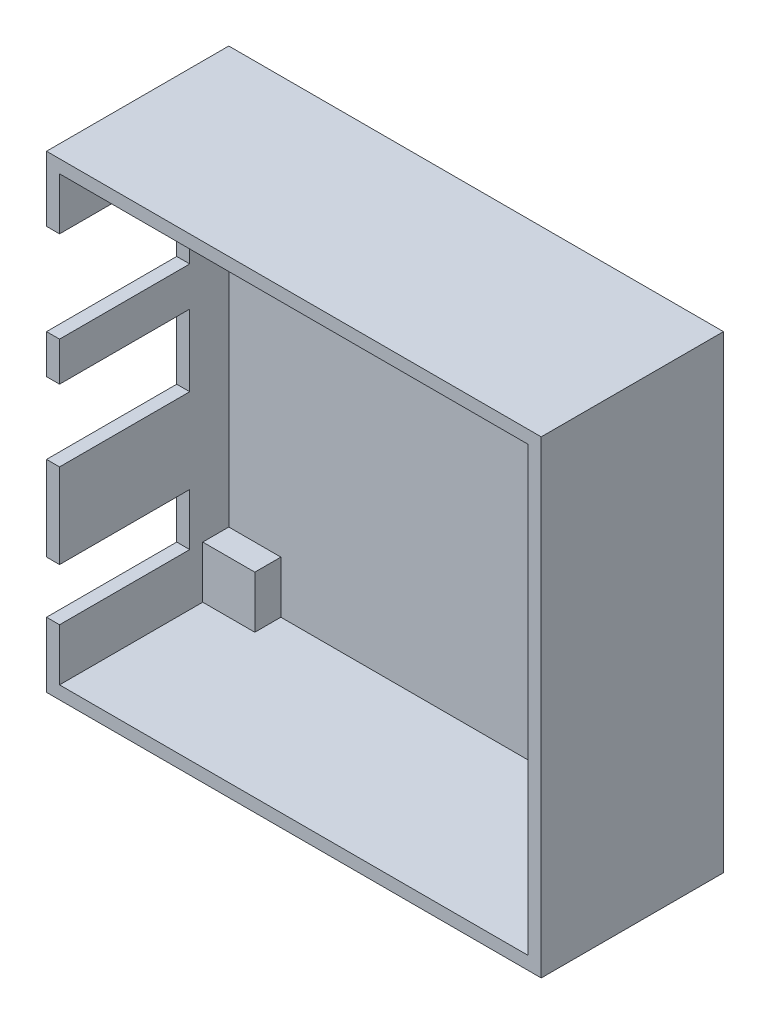
SolidWorks part; units mm, degrees
ref_plane "Plan de face" through (0, 0, 0) normal (0, 0, 1) x (1, 0, 0)
ref_plane "Plan de dessus" through (0, 0, 0) normal (0, 1, 0) x (1, 0, 0)
ref_plane "Plan de droite" through (0, 0, 0) normal (1, 0, 0) x (0, 0, -1)
sketch "Esquisse1" plane through (0, 0, 0) normal (0, 0, 1) x (1, 0, 0)
  line L1 (-70.1386, 46.5558) -> (5.8614, 46.5558)
  line L2 (-70.1386, 46.5558) -> (-70.1386, -25.4442)
  line L3 (-70.1386, -25.4442) -> (5.8614, -25.4442)
  line L4 (5.8614, 46.5558) -> (5.8614, -25.4442)
  dimension "D1" = 72
  dimension "D2" = 76
extrude "Boss.-Extru.1" add sketch "Esquisse1" along normal blind 2
sketch "Esquisse2" plane through (0, 0, 2) normal (0, 0, 1) x (1, 0, 0)
  line L1 (-70.1386, 46.5558) -> (5.8614, 46.5558)
  line L2 (-70.1386, 46.5558) -> (-70.1386, -25.4442)
  line L3 (-70.1386, -25.4442) -> (5.8614, -25.4442)
  line L4 (5.8614, 46.5558) -> (5.8614, -25.4442)
  line L5 (-68.1386, 44.5558) -> (3.8614, 44.5558)
  line L6 (-68.1386, 44.5558) -> (-68.1386, -23.4442)
  line L7 (-68.1386, -23.4442) -> (3.8614, -23.4442)
  line L8 (3.8614, 44.5558) -> (3.8614, -23.4442)
  dimension "D1" = 2
  dimension "D2" = 2
  dimension "D3" = 2
  dimension "D4" = 2
extrude "Boss.-Extru.2" add sketch "Esquisse2" along normal blind 26
sketch "Esquisse3" plane through (0, 0, 2) normal (0, 0, 1) x (1, 0, 0)
  line L0 (-68.1386, 44.5558) -> (-68.1386, -23.4442) construction
  line L1 (-68.1386, 44.5558) -> (-60.1386, 44.5558)
  line L2 (-68.1386, 44.5558) -> (-68.1386, 36.5558)
  line L3 (-68.1386, 36.5558) -> (-60.1386, 36.5558)
  line L4 (-60.1386, 44.5558) -> (-60.1386, 36.5558)
  line L5 (3.8614, -23.4442) -> (-4.1386, -23.4442)
  line L6 (3.8614, -23.4442) -> (3.8614, -15.4442)
  line L7 (3.8614, -15.4442) -> (-4.1386, -15.4442)
  line L8 (-4.1386, -23.4442) -> (-4.1386, -15.4442)
  line L9 (3.8614, 44.5558) -> (-4.1386, 44.5558)
  line L10 (3.8614, 44.5558) -> (3.8614, 36.5558)
  line L11 (3.8614, 36.5558) -> (-4.1386, 36.5558)
  line L12 (-4.1386, 44.5558) -> (-4.1386, 36.5558)
  line L13 (-68.1386, -23.4442) -> (-60.1386, -23.4442)
  line L14 (-68.1386, -23.4442) -> (-68.1386, -15.4442)
  line L15 (-68.1386, -15.4442) -> (-60.1386, -15.4442)
  line L16 (-60.1386, -23.4442) -> (-60.1386, -15.4442)
  line L17 (-68.1386, -23.4442) -> (3.8614, -23.4442) construction
  dimension "D3" = 8
extrude "Boss.-Extru.3" add sketch "Esquisse3" along normal blind 4
sketch3d "Esquisse3D1" plane through (0, 0, 0) normal (0, 0, 1) x (1, 0, 0)
  dimension "D1" = 2
sketch "Esquisse4" plane through (0, 0, 8) normal (0, 0, 1) x (1, 0, 0)
  line L0 (-68.1386, -23.4442) -> (3.8614, -23.4442) construction
  line L1 (-74.9001, -15.4442) -> (-62.4118, -15.4442)
  line L2 (-74.9001, -15.4442) -> (-74.9001, -7.4442)
  line L3 (-74.9001, -7.4442) -> (-62.4118, -7.4442)
  line L4 (-62.4118, -15.4442) -> (-62.4118, -7.4442)
  line L7 (-62.4118, 16.5558) -> (-74.278, 16.5558)
  line L8 (-62.4118, 16.5558) -> (-62.4118, 5.5558)
  line L9 (-62.4118, 5.5558) -> (-74.278, 5.5558)
  line L10 (-74.278, 16.5558) -> (-74.278, 5.5558)
  line L11 (-64.9729, 36.5558) -> (-76.918, 36.5558)
  line L12 (-64.9729, 36.5558) -> (-64.9729, 22.5558)
  line L13 (-64.9729, 22.5558) -> (-76.918, 22.5558)
  line L14 (-76.918, 36.5558) -> (-76.918, 22.5558)
  dimension "D1" = 8
  dimension "D2" = 8
  dimension "D3" = 11
  dimension "D4" = 29
  dimension "D5" = 46
  dimension "D6" = 14
extrude "Enlèv. mat.-Extru.1" cut sketch "Esquisse4" along normal through all
